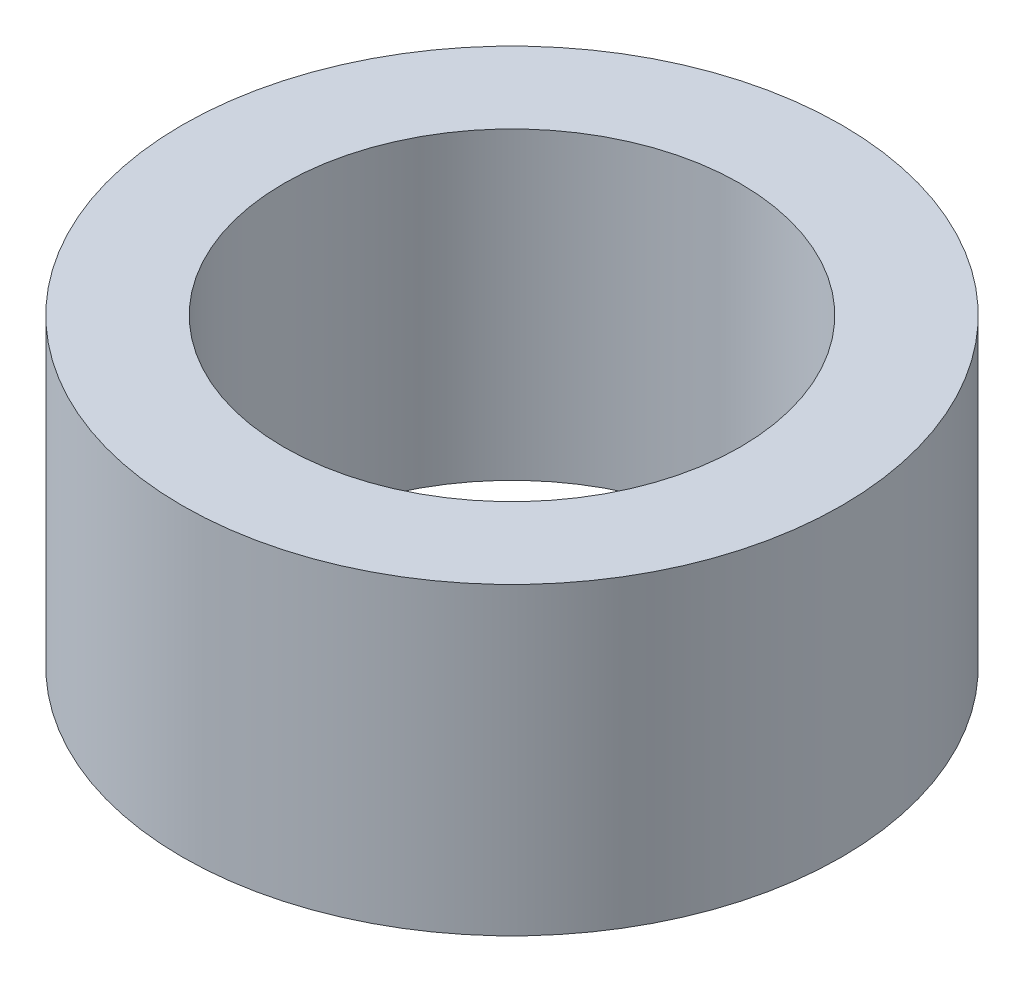
SolidWorks part; units mm, degrees
ref_plane "Front Plane" through (0, 0, 0) normal (0, 0, 1) x (1, 0, 0)
ref_plane "Top Plane" through (0, 0, 0) normal (0, 1, 0) x (1, 0, 0)
ref_plane "Right Plane" through (0, 0, 0) normal (1, 0, 0) x (0, 0, -1)
sketch "Sketch1" plane through (0, 0, 0) normal (0, 1, 0) x (1, 0, 0)
  circle A0 centre (0, 0) radius 2.25
  circle A1 centre (0, 0) radius 3.25
  dimension "D1" = 4.5
  dimension "D2" = 6.5
extrude "Boss-Extrude1" add sketch "Sketch1" along normal blind 3
